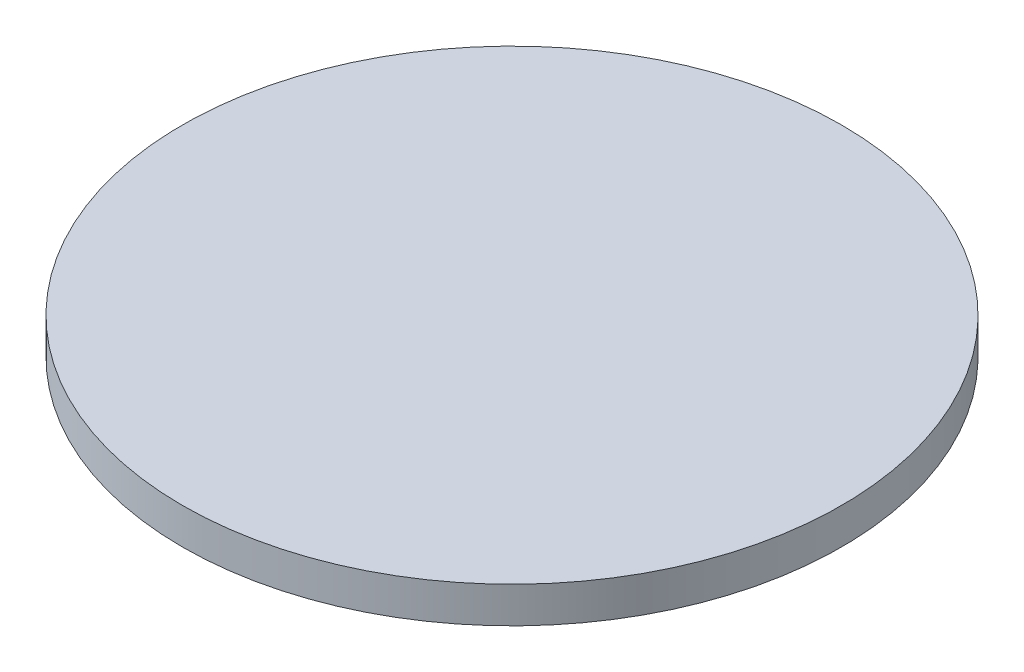
SolidWorks part; units mm, degrees
ref_plane "Front" through (0, 0, 0) normal (0, 0, 1) x (1, 0, 0)
ref_plane "Top" through (0, 0, 0) normal (0, 1, 0) x (1, 0, 0)
ref_plane "Right" through (0, 0, 0) normal (1, 0, 0) x (0, 0, -1)
sketch "Sketch1" plane through (0, 0, 0) normal (0, 1, 0) x (1, 0, 0)
  circle A0 centre (0, 0) radius 64
  dimension "D1" = 128
extrude "Boss-Extrude1" add sketch "Sketch1" along normal blind 7
